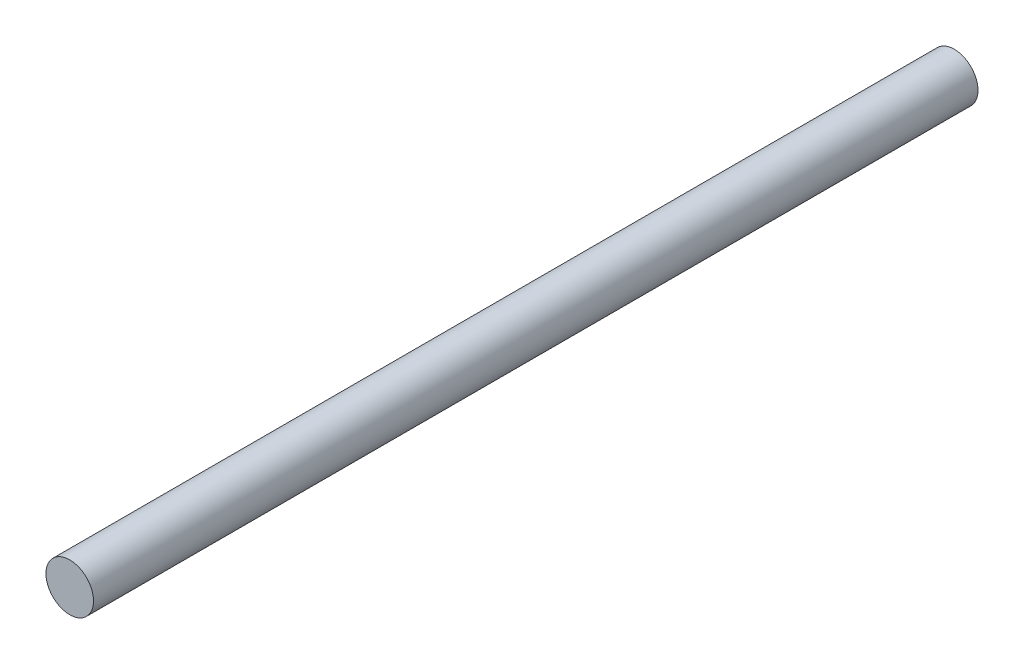
SolidWorks part; units mm, degrees
material "1060 Alloy"
ref_plane "Front Plane" through (0, 0, 0) normal (0, 0, 1) x (1, 0, 0)
ref_plane "Top Plane" through (0, 0, 0) normal (0, 1, 0) x (1, 0, 0)
ref_plane "Right Plane" through (0, 0, 0) normal (1, 0, 0) x (0, 0, -1)
sketch "Sketch1" plane through (0, 0, 0) normal (0, 0, 1) x (1, 0, 0)
  circle A0 centre (0, 0) radius 6.35
  dimension "D1" = 12.7
extrude "Boss-Extrude1" add sketch "Sketch1" along normal blind 236.22
